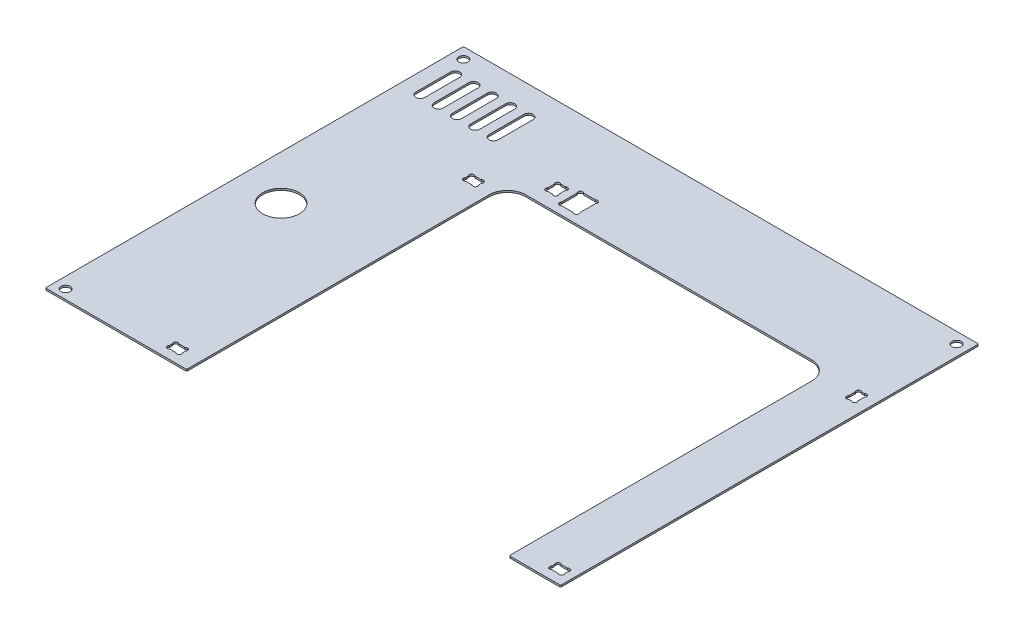
SolidWorks part; units mm, degrees
ref_plane "Front Plane" through (0, 0, 0) normal (0, 0, 1) x (1, 0, 0)
ref_plane "Top Plane" through (0, 0, 0) normal (0, 1, 0) x (1, 0, 0)
ref_plane "Right Plane" through (0, 0, 0) normal (1, 0, 0) x (0, 0, -1)
sketch "Sketch1" plane through (0, 0, 0) normal (0, 1, 0) x (1, 0, 0)
  line L0 (77, 0) -> (77, 175)
  line L1 (0, 0) -> (77, 0)
  line L5 (77, 175) -> (253, 175)
  line L6 (253, 175) -> (253, 0)
  line L7 (253, 0) -> (281, 0)
  line L8 (0, 0) -> (0, 228)
  line L9 (269.5, 10) -> (276.5, 10)
  line L10 (269.5, 10) -> (269.5, 5)
  line L11 (269.5, 5) -> (276.5, 5)
  line L12 (0, 228) -> (281, 228)
  line L13 (276.5, 10) -> (276.5, 5)
  line L14 (270, 173.5) -> (275, 173.5)
  line L15 (270, 173.5) -> (270, 166.5)
  line L16 (270, 166.5) -> (275, 166.5)
  line L17 (275, 173.5) -> (275, 166.5)
  line L18 (61, 10) -> (68, 10)
  line L19 (61, 10) -> (61, 5)
  line L20 (61, 5) -> (68, 5)
  line L21 (281, 228) -> (281, 0)
  line L23 (68, 10) -> (68, 5)
  line L24 (69.5, 165) -> (62.5, 165)
  line L25 (69.5, 165) -> (69.5, 170)
  line L26 (69.5, 170) -> (62.5, 170)
  line L27 (62.5, 165) -> (62.5, 170)
  circle A4 centre (24.25, 104.25) radius 10
  circle A5 centre (6, 222) radius 2.5
  circle A8 centre (6, 5) radius 2.5
  circle A13 centre (275, 222) radius 2.5
  dimension "D9" = 7
  dimension "D6" = 77
  dimension "D10" = 20
  dimension "D26" = 71
  dimension "D22" = 52.75
  dimension "D24" = 5
  dimension "D3" = 175
  dimension "D5" = 176
  dimension "D7" = 5
  dimension "D8" = 17
  dimension "D12" = 104.25
  dimension "D13" = 5
  dimension "D14" = 16.5
  dimension "D15" = 22
  dimension "D16" = 7
  dimension "D17" = 5
  dimension "D18" = 5
  dimension "D19" = 7
  dimension "D20" = 1.5
  dimension "D21" = 5
  dimension "D23" = 5
  dimension "D25" = 5
  dimension "D27" = 228
  dimension "D29" = 9
  dimension "D30" = 47
  dimension "D31" = 7
  dimension "D32" = 7.5
  dimension "D33" = 5
  dimension "D34" = 28
extrude "Boss-Extrude1" add sketch "Sketch1" along normal blind 1
fillet "Fillet1" radius 10 2 edges at (77, 0.5, -175) (253, 0.5, -175)
sketch "Sketch4" plane through (0, 1, 0) normal (0, 1, 0) x (1, 0, 0)
  line L0 (51, 212.5) -> (51, 193.5) construction
  line L1 (53.5, 212.5) -> (53.5, 193.5)
  line L2 (48.5, 212.5) -> (48.5, 193.5)
  line L3 (41, 212.5) -> (41, 193.5) construction
  line L4 (43.5, 212.5) -> (43.5, 193.5)
  line L5 (38.5, 212.5) -> (38.5, 193.5)
  line L6 (31, 212.5) -> (31, 193.5) construction
  line L7 (33.5, 212.5) -> (33.5, 193.5)
  line L8 (28.5, 212.5) -> (28.5, 193.5)
  line L9 (21, 212.5) -> (21, 193.5) construction
  line L10 (23.5, 212.5) -> (23.5, 193.5)
  line L11 (18.5, 212.5) -> (18.5, 193.5)
  line L12 (11, 212.5) -> (11, 193.5) construction
  line L13 (13.5, 212.5) -> (13.5, 193.5)
  line L14 (8.5, 212.5) -> (8.5, 193.5)
  line L16 (87, 175) -> (243, 175) construction
  arc A0 (53.5, 212.5) -> (48.5, 212.5) centre (51, 212.5) ccw
  arc A1 (48.5, 193.5) -> (53.5, 193.5) centre (51, 193.5) ccw
  arc A2 (43.5, 212.5) -> (38.5, 212.5) centre (41, 212.5) ccw
  arc A3 (38.5, 193.5) -> (43.5, 193.5) centre (41, 193.5) ccw
  arc A4 (33.5, 212.5) -> (28.5, 212.5) centre (31, 212.5) ccw
  arc A5 (28.5, 193.5) -> (33.5, 193.5) centre (31, 193.5) ccw
  arc A6 (23.5, 212.5) -> (18.5, 212.5) centre (21, 212.5) ccw
  arc A7 (18.5, 193.5) -> (23.5, 193.5) centre (21, 193.5) ccw
  arc A8 (13.5, 212.5) -> (8.5, 212.5) centre (11, 212.5) ccw
  arc A9 (8.5, 193.5) -> (13.5, 193.5) centre (11, 193.5) ccw
  circle A10 centre (6, 222) radius 2.5 construction
  point P2 (51, 203)
  point P7 (41, 203)
  point P14 (31, 203)
  point P23 (21, 203)
  point P30 (11, 203)
  dimension "D1" = 5
  dimension "D2" = 19
  dimension "D3" = 10
  dimension "D4" = 10
  dimension "D5" = 10
  dimension "D6" = 10
  dimension "D8" = 5
  dimension "D9" = 37.5
extrude "Cut-Extrude3" cut sketch "Sketch4" against normal through all
sketch "Sketch5" plane through (0, 1, 0) normal (0, 1, 0) x (1, 0, 0)
  line L0 (118.7297, 221.45) -> (118.7297, 190.45) construction
  line L1 (118.7297, 190.45) -> (87.7297, 190.45) construction
  line L2 (87.7297, 190.45) -> (87.7297, 221.45) construction
  line L3 (87.7297, 221.45) -> (118.7297, 221.45) construction
sketch "Sketch6" plane through (0, 1, 0) normal (0, 1, 0) x (1, 0, 0)
  line L0 (100.19, 179.6) -> (110.19, 191.6) construction
  line L1 (100.19, 191.6) -> (110.19, 179.6) construction
  line L2 (281, 0) -> (281, 228) construction
  line L3 (100.19, 179.6) -> (110.19, 179.6)
  line L5 (87, 175) -> (243, 175) construction
  line L7 (100.19, 191.6) -> (110.19, 191.6)
  line L8 (100.19, 191.6) -> (100.19, 179.6)
  line L9 (110.19, 191.6) -> (110.19, 179.6)
  point P2 (87, 179.6)
  point P3 (243, 179.6)
  point P6 (105.19, 185.6)
  point P8 (105.19, 228)
  point P9 (105.19, 175)
  point P11 (87, 189.6)
  point P12 (243, 189.6)
  point P13 (100.19, 228)
  point P14 (100.19, 175)
  point P15 (110.19, 228)
  point P16 (110.19, 175)
  dimension "D2" = 10
  dimension "D1" = 12
  dimension "D3" = 4.6
  dimension "D4" = 10
  dimension "D5" = 12
  dimension "D6" = 175.81
extrude "Cut-Extrude5" cut sketch "Sketch6" against normal blind 10
sketch "Sketch7" plane through (0, 1, 0) normal (0, 1, 0) x (1, 0, 0)
  line L0 (89.74, 182.6) -> (95.74, 182.6)
  line L1 (95.74, 189.6) -> (95.74, 182.6)
  line L2 (89.74, 189.6) -> (89.74, 182.6)
  line L3 (95.74, 202.9944) -> (95.74, 171.1862) construction
  line L4 (89.74, 189.6) -> (95.74, 189.6)
  line L5 (100.19, 191.6) -> (100.19, 179.6) construction
  line L6 (89.74, 202.9944) -> (89.74, 171.1862) construction
  line L7 (87, 175) -> (243, 175) construction
  line L9 (281, 228) -> (0, 228) construction
  dimension "D1" = 7.6
  dimension "D3" = 38.4
  dimension "D4" = 4.45
extrude "Cut-Extrude6" cut sketch "Sketch7" against normal through all
sketch "Sketch3" plane through (0, 1, 0) normal (0, 1, 0) x (1, 0, 0)
  line L0 (276.5, 7.5) -> (273, 7.5) construction
  line L1 (62.5, 165.8839) -> (63.3839, 165.8839) construction
  line L2 (276.5, 5) -> (276.5, 10) construction
  line L3 (273, 7.5) -> (273, 5) construction
  line L4 (269.5, 5) -> (276.5, 5) construction
  line L5 (63.3839, 165.8839) -> (63.3839, 165) construction
  line L6 (276.5, 5.8839) -> (275.6161, 5.8839) construction
  line L7 (275.6161, 5.8839) -> (275.6161, 5) construction
  line L8 (269.5, 10) -> (269.5, 5) construction
  line L9 (62.5, 165) -> (69.5, 165) construction
  line L10 (168.75, 5) -> (168.75, 25.6874) construction
  line L11 (68, 5) -> (68, 10) construction
  line L12 (272.5, 166.5) -> (272.5, 170) construction
  line L13 (62.5, 167.5) -> (65.2042, 167.5) construction
  line L14 (270, 166.5) -> (275, 166.5) construction
  line L15 (272.5, 170) -> (275, 170) construction
  line L16 (275, 166.5) -> (275, 173.5) construction
  line L17 (275, 167.3839) -> (274.1161, 167.3839) construction
  line L18 (274.1161, 167.3839) -> (274.1161, 166.5) construction
  line L19 (62.5, 170) -> (62.5, 165) construction
  line L20 (66, 165) -> (66, 166.3504) construction
  line L22 (95.74, 189.6) -> (89.74, 189.6) construction
  line L23 (100.19, 191.6) -> (110.19, 179.6) construction
  line L24 (110.19, 191.6) -> (100.19, 179.6) construction
  line L26 (105.19, 191.6) -> (105.19, 179.6) construction
  line L27 (89.74, 189.6) -> (89.74, 182.6) construction
  line L28 (92.74, 189.6) -> (92.74, 182.6) construction
  line L29 (89.74, 182.6) -> (95.74, 182.6) construction
  line L30 (89.74, 186.1) -> (95.74, 186.1) construction
  line L31 (95.74, 182.6) -> (95.74, 189.6) construction
  line L32 (101.0739, 190.7161) -> (101.0739, 191.6) construction
  line L33 (110.19, 191.6) -> (100.19, 191.6) construction
  line L34 (101.0739, 190.7161) -> (100.19, 190.7161) construction
  line L35 (100.19, 179.6) -> (110.19, 179.6) construction
  line L36 (100.19, 191.6) -> (100.19, 179.6) construction
  line L39 (100.19, 185.6) -> (110.19, 185.6) construction
  line L40 (110.19, 179.6) -> (110.19, 191.6) construction
  circle A0 centre (275.6161, 5.8839) radius 1.25
  circle A1 centre (275.6161, 9.1161) radius 1.25
  circle A2 centre (270.3839, 9.1161) radius 1.25
  circle A3 centre (270.3839, 5.8839) radius 1.25
  circle A4 centre (274.1161, 167.3839) radius 1.25
  circle A5 centre (270.8839, 167.3839) radius 1.25
  circle A6 centre (274.1161, 172.6161) radius 1.25
  circle A7 centre (270.8839, 172.6161) radius 1.25
  circle A8 centre (67.1161, 9.1161) radius 1.25
  circle A9 centre (67.1161, 5.8839) radius 1.25
  circle A10 centre (61.8839, 5.8839) radius 1.25
  circle A11 centre (61.8839, 9.1161) radius 1.25
  circle A12 centre (63.3839, 165.8839) radius 1.25
  circle A13 centre (63.3839, 169.1161) radius 1.25
  circle A14 centre (68.6161, 169.1161) radius 1.25
  circle A15 centre (68.6161, 165.8839) radius 1.25
  circle A16 centre (90.62, 188.72) radius 1.25
  circle A17 centre (94.86, 188.72) radius 1.25
  circle A18 centre (90.62, 183.48) radius 1.25
  circle A19 centre (94.86, 183.48) radius 1.25
  circle A20 centre (101.0739, 190.7161) radius 1.25
  circle A21 centre (109.3061, 180.4839) radius 1.25
  circle A22 centre (109.3061, 190.7161) radius 1.25
  circle A23 centre (101.0739, 180.4839) radius 1.25
  dimension "D1" = 2.5
  dimension "D4" = 2.5
  dimension "D6" = 0.88
  dimension "D2" = 2.5
  dimension "D3" = 2.5
  dimension "D5" = 0.88
extrude "Cut-Extrude2" cut sketch "Sketch3" against normal through all
fillet "Fillet2" radius 0.5 6 edges at (0, 0.5, 0) (253, 0.5, 0) (281, 0.5, 0) (77, 0.5, 0) (281, 0.5, -228) (0, 0.5, -228)
